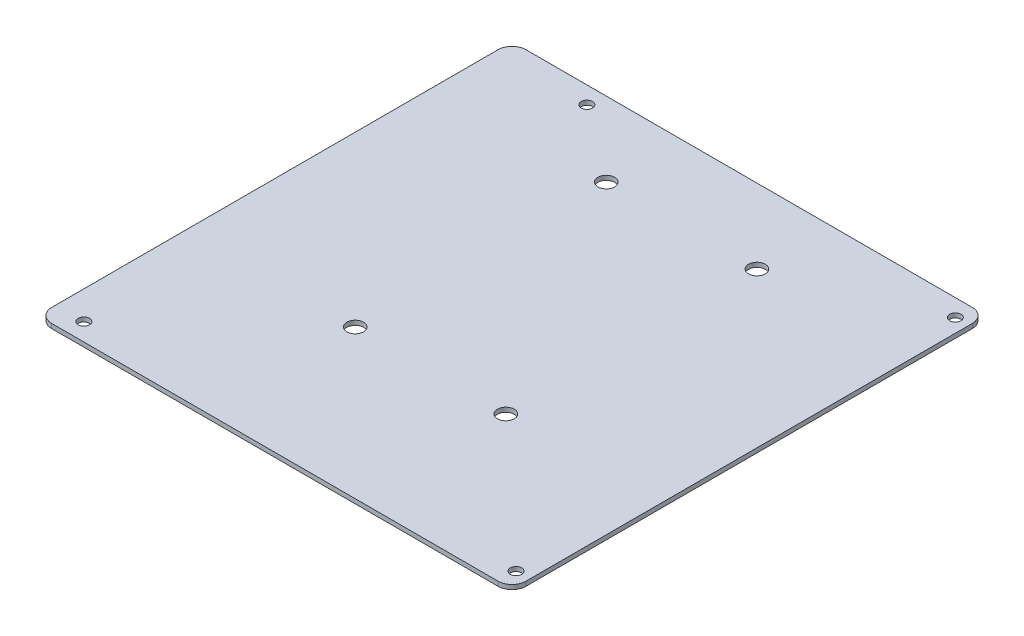
SolidWorks part; units mm, degrees
ref_plane "Front Plane" through (0, 0, 0) normal (0, 0, 1) x (1, 0, 0)
ref_plane "Top Plane" through (0, 0, 0) normal (0, 1, 0) x (1, 0, 0)
ref_plane "Right Plane" through (0, 0, 0) normal (1, 0, 0) x (0, 0, -1)
sketch "Sketch1" plane through (0, 0, 0) normal (0, 1, 0) x (1, 0, 0)
  line L1 (-85, -85) -> (85, -85)
  line L2 (-85, -85) -> (-85, 85)
  line L3 (-85, 85) -> (85, 85)
  line L4 (85, -85) -> (85, 85)
  line L5 (-85, -85) -> (85, 85) construction
  line L6 (-85, 85) -> (85, -85) construction
  point P0 (0, 0)
  dimension "D1" = 170
  dimension "D2" = 170
extrude "base pcb" add sketch "Sketch1" along normal blind 1.6
fillet "pcb rounded corners" radius 5 4 edges at (85, 0.8, -85) (-85, 0.8, -85) (-85, 0.8, 85) (85, 0.8, 85)
sketch "Sketch3" plane through (0, 1.6, 0) normal (0, 1, 0) x (1, 0, 0)
  line L0 (-80, -85) -> (80, -85) construction
  line L3 (-85, 80) -> (-85, -80) construction
  circle A0 centre (-74.84, -78.65) radius 2.032
  circle A1 centre (80.1, -78.65) radius 2.032
  circle A2 centre (80.1, 78.83) radius 2.032
  circle A3 centre (-51.98, 78.83) radius 2.032
  dimension "D1" = 6.35
  dimension "D2" = 6.35
  dimension "D3" = 157.48
  dimension "D4" = 157.48
  dimension "D5" = 154.94
  dimension "D6" = 0
  dimension "D7" = 10.16
  dimension "D8" = 22.86
  dimension "D9" = 4.064
  dimension "D10" = 4.064
  dimension "D11" = 4.064
  dimension "D12" = 4.064
extrude "mounting holes" cut sketch "Sketch3" against normal blind 1.6
sketch "Sketch4" plane through (0, 1.6, 0) normal (0, 1, 0) x (1, 0, 0)
  line L0 (80, 85) -> (-80, 85) construction
  line L1 (85, -80) -> (85, 80) construction
  circle A0 centre (-24.5, 58.3) radius 3
  circle A1 centre (29.5, 58.3) radius 3
  circle A2 centre (-24.5, -31.7) radius 3
  circle A3 centre (29.5, -31.7) radius 3
  dimension "D1" = 54
  dimension "D2" = 54
  dimension "D3" = 90
  dimension "D4" = 90
  dimension "D5" = 26.7
  dimension "D6" = 26.7
  dimension "D7" = 55.5
  dimension "D8" = 55.5
  dimension "D9" = 6
  dimension "D10" = 6
  dimension "D11" = 6
  dimension "D12" = 6
extrude "Cut-Extrude1" cut sketch "Sketch4" against normal blind 10
